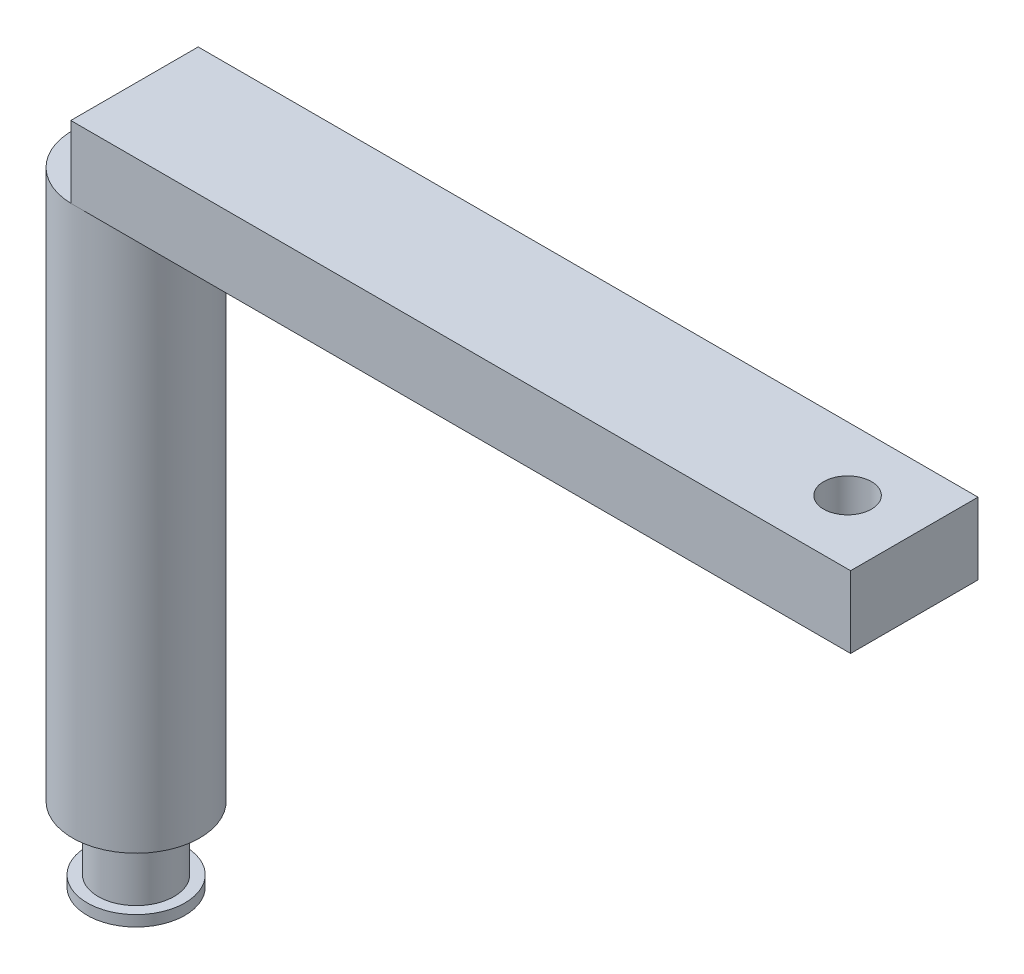
SolidWorks part; units mm, degrees
ref_plane "Front" through (0, 0, 0) normal (0, 0, 1) x (1, 0, 0)
ref_plane "Top" through (0, 0, 0) normal (0, 1, 0) x (1, 0, 0)
ref_plane "Right" through (0, 0, 0) normal (1, 0, 0) x (0, 0, -1)
sketch "Sketch1" plane through (-14.7776, 30.2148, 34.5615) normal (0.9997, 0, 0.0253) x (-0.0253, 0, 0.9997)
  line L0 (-0.7943, 0.007) -> (-0.7943, 2.2852) construction
  line L1 (0.5385, -0.016) -> (-0.7943, -0.016)
  line L2 (-0.7943, 12.7963) -> (-0.7943, -0.016)
  line L5 (0.5385, -0.016) -> (0.5385, 11.466)
  line L6 (0.5385, 11.466) -> (-0.0006, 11.466)
  line L7 (-0.0006, 11.684) -> (-0.0006, 0.007) construction
  line L8 (-0.0006, 11.466) -> (-0.0006, 12.7963)
  line L9 (-0.7943, -0.1737) -> (-0.7943, -1.5665) construction
  line L10 (-0.0006, 12.7963) -> (0.2284, 12.7963)
  line L11 (0.2284, 12.7963) -> (0.2284, 13.0227)
  line L12 (0.2284, 13.0227) -> (-0.7943, 13.0227)
  line L13 (-0.7943, 13.0227) -> (-0.7943, 12.7963)
revolve "Revolve1" add sketch "Sketch1" angle 360 about L9
sketch "Sketch5" plane through (0, 30.2309, 0) normal (0, 1, 0) x (1, 0, 0)
  line L0 (-15.0991, -47.2499) -> (-14.7776, -34.561) construction
  line L1 (-14.7238, -32.4351) -> (-14.7913, -32.4351)
  line L2 (-14.7238, -32.4351) -> (-14.7238, -35.0998) construction
  line L3 (-14.7238, -35.0998) -> (-14.7913, -35.0998)
  line L4 (-14.7913, -32.4351) -> (-14.7913, -35.0998)
  line L5 (-14.7238, -32.4351) -> (-14.7913, -35.0998) construction
  line L6 (-14.7238, -35.0998) -> (-14.7913, -32.4351) construction
  line L7 (-14.7238, -32.4351) -> (1.5212, -32.4351)
  line L8 (-14.7238, -35.0998) -> (1.5212, -35.0998)
  line L9 (1.5212, -35.0998) -> (1.5212, -32.4351)
  line L10 (-14.7575, -33.7675) -> (4.4862, -33.7675) construction
  circle A0 centre (0, -33.7675) radius 0.75
  circle A1 centre (-14.7575, -33.7675) radius 1.3328
  circle A2 centre (-14.7575, -33.7675) radius 1.3328 construction
  dimension "D2" = 1.5
  dimension "D1" = 0
extrude "Boss-Extrude1" add sketch "Sketch5" along normal blind 1.5 contours L7 L9 L8 L3 L4 L1
sketch "Sketch6" plane through (0, 30.2309, 0) normal (0, -1, 0) x (1, 0, 0)
  line L0 (1.5212, 33.7675) -> (-1.2708, 33.7675) construction
  line L1 (1.5212, 35.0998) -> (1.5212, 32.4351) construction
  circle A0 centre (-14.7575, 33.7675) radius 13.4867 construction
  circle A1 centre (0.1252, 33.7675) radius 0.5
  dimension "D1" = 1
extrude "Cut-Extrude1" cut sketch "Sketch6" against normal through all and the other way through all contours A1
